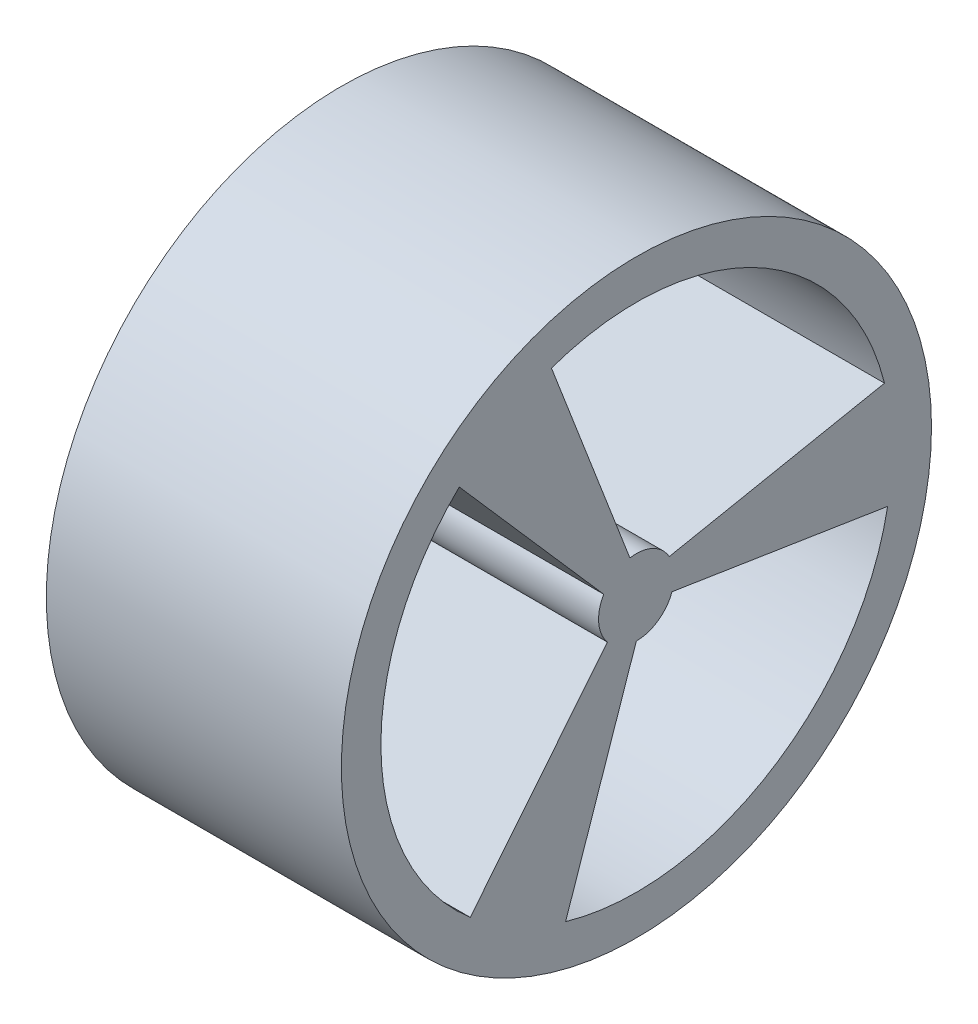
SolidWorks part; units mm, degrees
ref_plane "Front Plane" through (0, 0, 0) normal (0, 0, 1) x (1, 0, 0)
ref_plane "Top Plane" through (0, 0, 0) normal (0, 1, 0) x (1, 0, 0)
ref_plane "Right Plane" through (0, 0, 0) normal (1, 0, 0) x (0, 0, -1)
sketch "Sketch1" plane through (0, 0, 0) normal (1, 0, 0) x (0, 0, -1)
  circle A0 centre (0, 0) radius 10
  dimension "D1" = 20
extrude "Boss-Extrude1" add sketch "Sketch1" along normal blind 10
sketch "Sketch2" plane through (10, 0, 0) normal (1, 0, 0) x (0, 0, -1)
  line L0 (-6.0053, 6.2398) -> (-1.1101, 0.6451)
  line L1 (-5.6326, -6.5782) -> (-0.9845, -0.8241)
  line L2 (8.4065, 2.0809) -> (1.1137, 0.6388)
  line L3 (-2.8806, 8.1671) -> (-0.2214, 1.2647)
  line L4 (-2.4011, -8.3207) -> (-0.0036, -1.2839)
  line L5 (8.5132, -1.5889) -> (1.2059, -0.4406)
  arc A0 (-6.0053, 6.2398) -> (-5.6326, -6.5782) centre (0, 0) ccw
  arc A1 (-0.9845, -0.8241) -> (-1.1101, 0.6451) centre (0, 0) cw
  circle A2 centre (0, 0) radius 10 construction
  arc A3 (-0.2214, 1.2647) -> (1.1137, 0.6388) centre (0, 0) cw
  arc A4 (8.4065, 2.0809) -> (-2.8806, 8.1671) centre (0, 0) ccw
  arc A5 (1.2059, -0.4406) -> (-0.0036, -1.2839) centre (0, 0) cw
  arc A6 (-2.4011, -8.3207) -> (8.5132, -1.5889) centre (0, 0) ccw
  point P8 (-6.0608, 6.3031)
  point P9 (-5.6326, -6.5782)
  point P17 (0, 0)
  dimension "D1" = 3
extrude "Cut-Extrude1" cut sketch "Sketch2" against normal through all both
